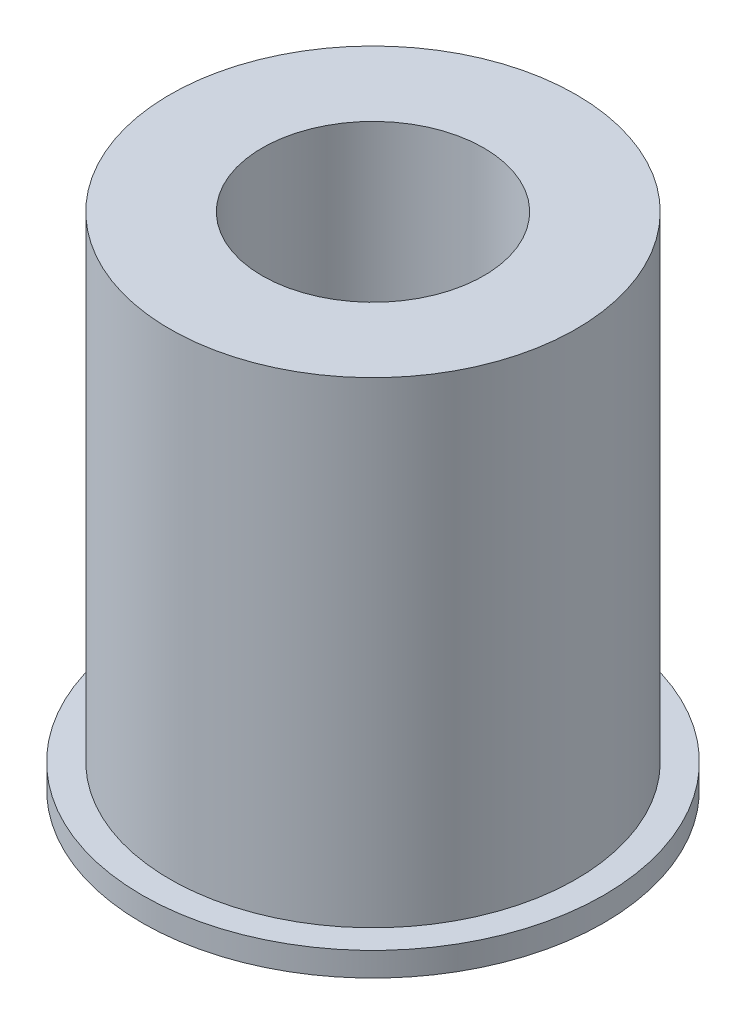
SolidWorks part; units mm, degrees
ref_plane "Front Plane" through (0, 0, 0) normal (0, 0, 1) x (1, 0, 0)
ref_plane "Top Plane" through (0, 0, 0) normal (0, 1, 0) x (1, 0, 0)
ref_plane "Right Plane" through (0, 0, 0) normal (1, 0, 0) x (0, 0, -1)
sketch "Sketch1" plane through (0, 0, 0) normal (0, 1, 0) x (1, 0, 0)
  circle A2 centre (0, 0) radius 11
  dimension "D1" = 22
extrude "Boss-Extrude1" add sketch "Sketch1" along normal blind 27.1
sketch "Sketch2" plane through (0, 0, 0) normal (0, 1, 0) x (1, 0, 0)
  circle A0 centre (0, 0) radius 12.5
extrude "Boss-Extrude2" add sketch "Sketch2" along normal blind 1.3
sketch "Sketch3" plane through (0, 0, 0) normal (0, 1, 0) x (1, 0, 0)
  circle A0 centre (0, 0) radius 6
  dimension "D1" = 12
extrude "Cut-Extrude1" cut sketch "Sketch3" along normal blind 29.3
